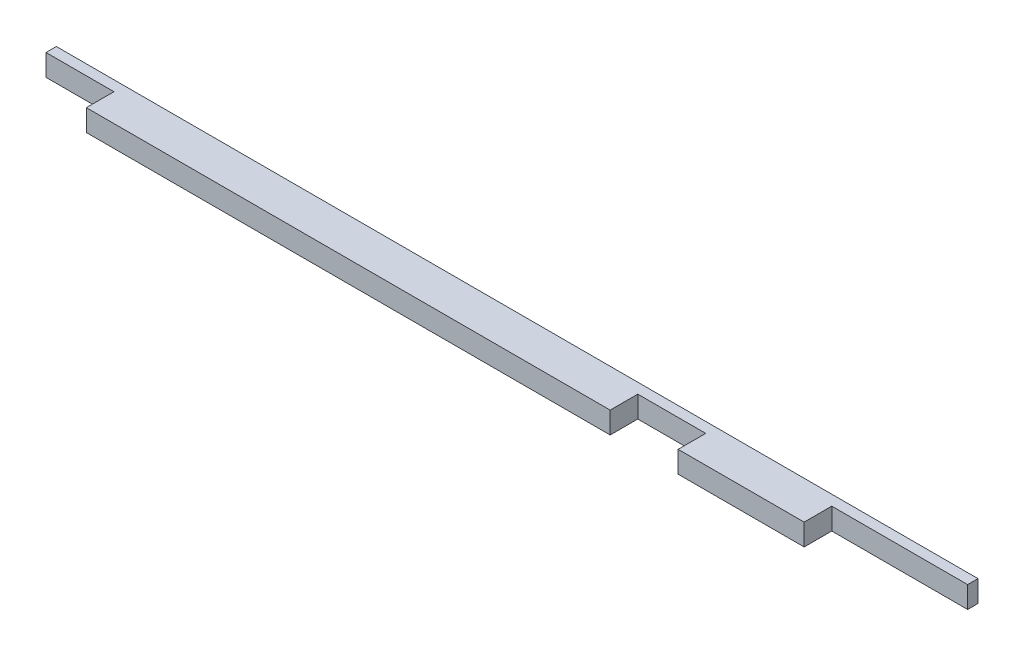
SolidWorks part; units mm, degrees
ref_plane "Front Plane" through (0, 0, 0) normal (0, 0, 1) x (1, 0, 0)
ref_plane "Top Plane" through (0, 0, 0) normal (0, 1, 0) x (1, 0, 0)
ref_plane "Right Plane" through (0, 0, 0) normal (1, 0, 0) x (0, 0, -1)
sketch "Sketch1" plane through (0, 0, 0) normal (0, 1, 0) x (1, 0, 0)
  line L0 (5, 0) -> (43.5513, 0)
  line L1 (0, 2.794) -> (67.8269, 2.794)
  line L2 (10, 2.032) -> (10, 0) construction
  line L3 (0, 2.032) -> (67.8269, 2.032) construction
  line L4 (0, 2.794) -> (0, 0) construction
  line L5 (43.5513, 2.032) -> (48.5513, 2.032)
  line L6 (57.8269, 2.032) -> (57.8269, 0)
  line L7 (19.2756, 2.032) -> (19.2756, 0) construction
  line L8 (48.5513, 2.032) -> (48.5513, 0)
  line L9 (29.2756, 2.032) -> (29.2756, 0) construction
  line L10 (38.5513, 2.032) -> (38.5513, 0)
  line L11 (5, 0) -> (5, 2.032)
  line L12 (43.5513, 0) -> (43.5513, 2.032)
  line L13 (48.5513, 0) -> (57.8269, 0)
  line L14 (67.8269, 2.794) -> (67.8269, 2.032)
  line L15 (57.8269, 2.032) -> (67.8269, 2.032)
  line L16 (0, 2.032) -> (5, 2.032)
  line L17 (0, 2.794) -> (0, 2.032)
  dimension "D2" = 10
  dimension "D3" = 2.794
  dimension "D4" = 0.762
  dimension "D5" = 67.8269
  dimension "D6" = 5
  dimension "D7" = 9.2756
  dimension "D8" = 9.2756
  dimension "D9" = 10
  dimension "D10" = 10
  dimension "D11" = 9.2756
  dimension "D12" = 5
  dimension "D13" = 10
extrude "Boss-Extrude1" add sketch "Sketch1" along normal blind 1.5875
